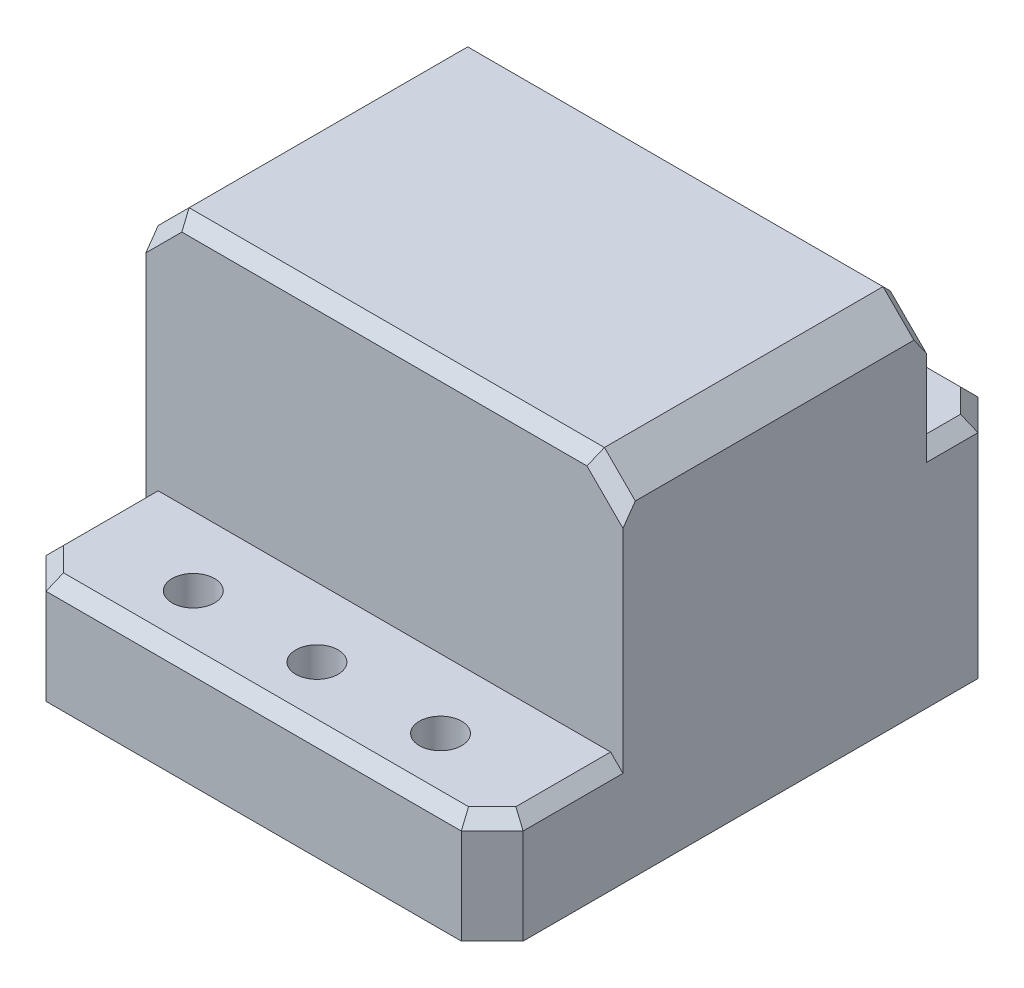
SolidWorks part; units mm, degrees
ref_plane "Front Plane" through (0, 0, 0) normal (0, 0, 1) x (1, 0, 0)
ref_plane "Top Plane" through (0, 0, 0) normal (0, 1, 0) x (1, 0, 0)
ref_plane "Right Plane" through (0, 0, 0) normal (1, 0, 0) x (0, 0, -1)
sketch "Sketch1" plane through (0, 0, 0) normal (1, 0, 0) x (0, 0, -1)
  line L0 (19.3431, 8.6897) -> (27.8325, 8.6897)
  line L2 (-25.2535, -3.385) -> (-25.2535, -14.4536)
  line L3 (-25.2535, -14.4536) -> (27.8325, -14.4536)
  line L4 (27.8325, 8.6897) -> (27.8325, -14.4536)
  line L5 (-11.8208, 22.1224) -> (19.3431, 22.1224)
  line L6 (-11.8208, 22.1224) -> (-11.8208, -3.385)
  line L8 (19.3431, 22.1224) -> (19.3431, 8.6897)
  line L10 (-25.2535, -3.385) -> (-11.8208, -3.385)
  dimension "D1" = 53.086
  dimension "D2" = 36.576
extrude "Boss-Extrude1" add sketch "Sketch1" along normal blind 49.022
chamfer "Chamfer4" distance 3.175 angle 45 1 edges at (0, 22.1224, -3.7612)
chamfer "Chamfer5" distance 3.175 angle 45 1 edges at (49.022, 22.1224, -3.7612)
chamfer "Chamfer6" distance 3.175 angle 45 4 edges at (49.022, -2.8819, -27.8325) (49.022, -8.9193, 25.2535) (0, -8.9193, 25.2535) (0, -2.8819, -27.8325)
sketch "Sketch4" plane through (0, -3.385, 0) normal (0, 1, 0) x (1, 0, 0)
  circle A0 centre (24.6653, -18.9081) radius 2.1784
  circle A1 centre (37.3653, -18.9081) radius 2.1784
  circle A2 centre (11.9653, -18.9081) radius 2.1784
  dimension "D1" = 2
  dimension "D2" = 2
extrude "Cut-Extrude1" cut sketch "Sketch4" against normal blind 5.08 contours A1 | A0 | A2
chamfer "Chamfer7" distance 1.27 angle 45 5 edges at (49.022, 8.6897, -22.0003) (47.4345, 8.6897, -26.245) (24.511, 8.6897, -27.8325) (1.5875, 8.6897, -26.245) (0, 8.6897, -22.0003)
chamfer "Chamfer8" distance 1.27 angle 45 5 edges at (49.022, -3.385, 16.9496) (47.4345, -3.385, 23.666) (24.511, -3.385, 25.2535) (1.5875, -3.385, 23.666) (0, -3.385, 16.9496)
chamfer "Chamfer9" distance 1.27 angle 45 6 edges at (1.5875, 20.5349, -19.3431) (24.511, 22.1224, -19.3431) (47.4345, 20.5349, -19.3431) (47.4345, 20.5349, 11.8208) (24.511, 22.1224, 11.8208) (1.5875, 20.5349, 11.8208)
